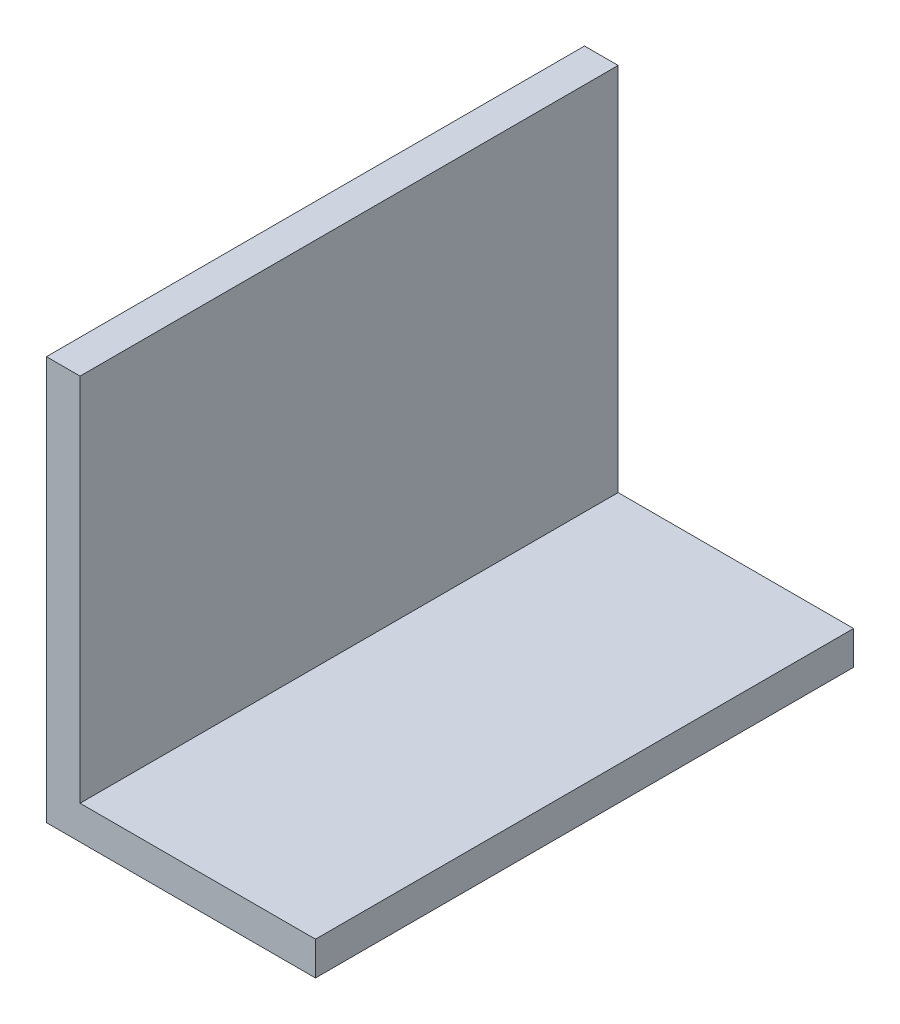
SolidWorks part; units mm, degrees
ref_plane "Front Plane" through (0, 0, 0) normal (0, 0, 1) x (1, 0, 0)
ref_plane "Top Plane" through (0, 0, 0) normal (0, 1, 0) x (1, 0, 0)
ref_plane "Right Plane" through (0, 0, 0) normal (1, 0, 0) x (0, 0, -1)
sketch "Sketch1" plane through (0, 0, 0) normal (0, 0, 1) x (1, 0, 0)
  line L0 (0, 0) -> (0, 38.1)
  line L1 (0, 0) -> (25.4, 0)
  dimension "D1" = 38.1
  dimension "D2" = 25.4
extrude "Extrude-Thin1" add sketch "Sketch1" along normal blind 50.8 thin
